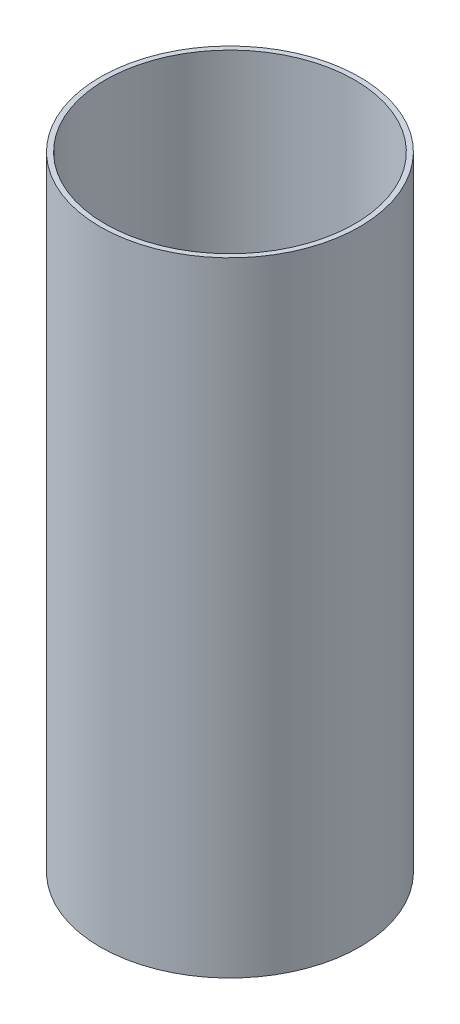
SolidWorks part; units mm, degrees
ref_plane "Front Plane" through (0, 0, 0) normal (0, 0, 1) x (1, 0, 0)
ref_plane "Top Plane" through (0, 0, 0) normal (0, 1, 0) x (1, 0, 0)
ref_plane "Right Plane" through (0, 0, 0) normal (1, 0, 0) x (0, 0, -1)
sketch "Sketch2" plane through (0, 0, 0) normal (0, 1, 0) x (1, 0, 0)
  circle A0 centre (0, 0) radius 38.1
  circle A1 centre (0, 0) radius 39.624
  dimension "D1" = 79.248
  dimension "D2" = 76.2
extrude "Boss-Extrude1" add sketch "Sketch2" along normal blind 190.5
